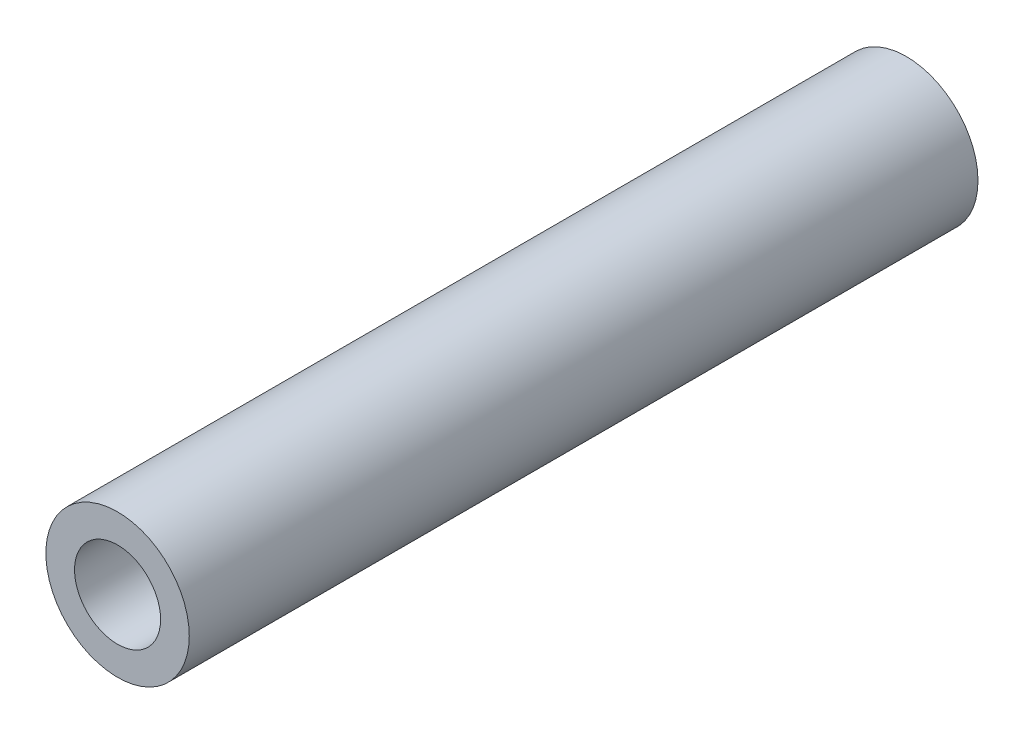
SolidWorks part; units mm, degrees
ref_plane "Front Plane" through (0, 0, 0) normal (0, 0, 1) x (1, 0, 0)
ref_plane "Top Plane" through (0, 0, 0) normal (0, 1, 0) x (1, 0, 0)
ref_plane "Right Plane" through (0, 0, 0) normal (1, 0, 0) x (0, 0, -1)
sketch "Sketch1" plane through (0, 0, 0) normal (0, 0, 1) x (1, 0, 0)
  circle A0 centre (0, 0) radius 2.5
extrude "Boss-Extrude1" add sketch "Sketch1" along normal blind 25 and the other way blind 2.5
sketch "Sketch2" plane through (0, 0, 25) normal (0, 0, 1) x (1, 0, 0)
  circle A0 centre (0, 0) radius 1.5
sketch "Sketch3" plane through (0, 0, -2.5) normal (0, 0, -1) x (-1, 0, 0)
  circle A0 centre (0, 0) radius 1.5
extrude "Cut-Extrude1" cut sketch "Sketch3" against normal blind 6 contours A0
extrude "Cut-Extrude2" cut sketch "Sketch2" against normal blind 6 contours A0
